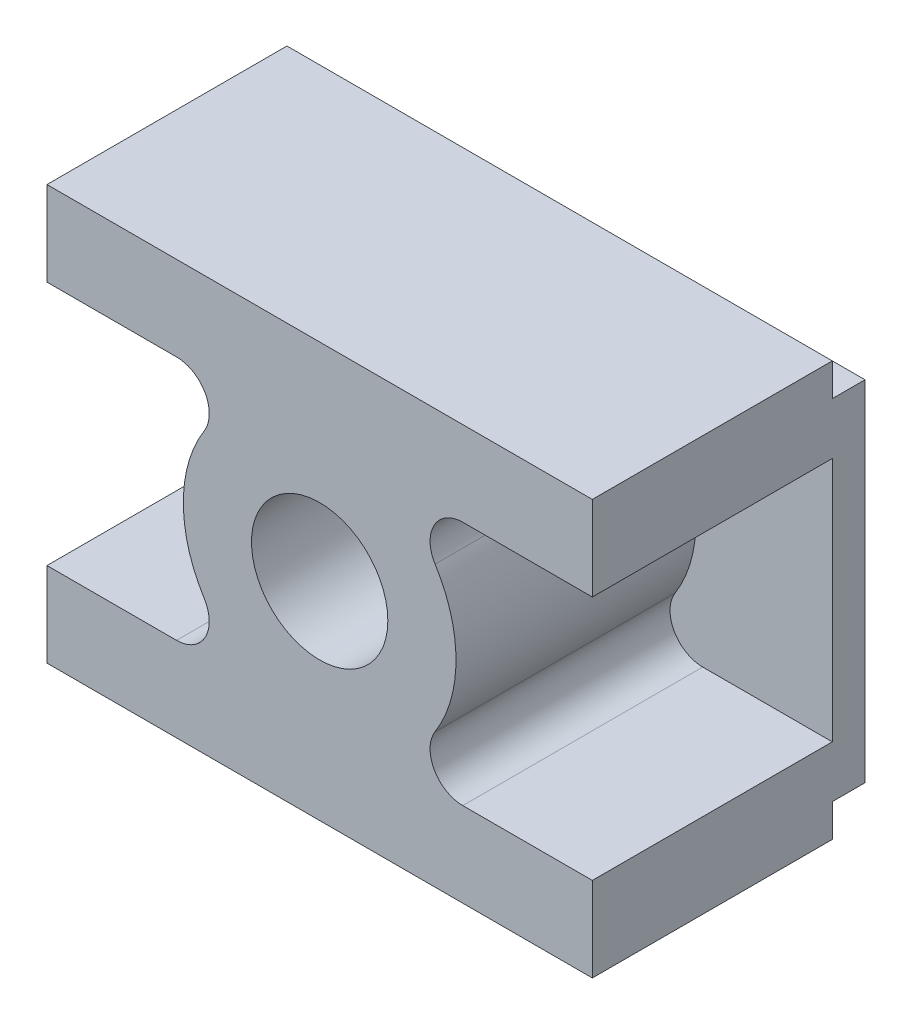
SolidWorks part; units mm, degrees
material "AISI 304"
ref_plane "Front Plane" through (0, 0, 0) normal (0, 0, 1) x (1, 0, 0)
ref_plane "Top Plane" through (0, 0, 0) normal (0, 1, 0) x (1, 0, 0)
ref_plane "Right Plane" through (0, 0, 0) normal (1, 0, 0) x (0, 0, -1)
sketch "Sketch1" plane through (0, 0, 0) normal (0, 0, 1) x (1, 0, 0)
  line L0 (26.244, 22.5) -> (50, 22.5)
  line L1 (-50, -38) -> (50, -38)
  line L2 (-50, -38) -> (-50, 38)
  line L3 (-50, 38) -> (50, 38)
  line L4 (50, -38) -> (50, 38)
  line L5 (-50, -38) -> (50, 38) construction
  line L6 (-50, 38) -> (50, -38) construction
  line L7 (-50, 22.5) -> (-26.244, 22.5)
  line L8 (-50, -22.5) -> (-26.244, -22.5)
  line L9 (26.244, -22.5) -> (50, -22.5)
  line L10 (-39.8812, 0) -> (43.0416, 0) construction
  arc A0 (-21.1646, 13.3065) -> (-21.1646, -13.3065) centre (0, 0) ccw
  circle A1 centre (0, 0) radius 12.5
  arc A2 (21.1646, -13.3065) -> (21.1646, 13.3065) centre (0, 0) ccw
  arc A3 (21.1646, -13.3065) -> (26.244, -22.5) centre (26.244, -16.5) ccw
  arc A4 (-21.1646, -13.3065) -> (-26.244, -22.5) centre (-26.244, -16.5) cw
  arc A5 (-21.1646, 13.3065) -> (-26.244, 22.5) centre (-26.244, 16.5) ccw
  arc A6 (26.244, 22.5) -> (21.1646, 13.3065) centre (26.244, 16.5) ccw
  point P0 (0, 0)
  point P15 (10.8972, -22.5)
  point P27 (10.8972, 22.5)
  dimension "D5" = 25
  dimension "D6" = 50
  dimension "D3" = 6
  dimension "D1" = 76
  dimension "D2" = 100
  dimension "D7" = 45
extrude "Boss-Extrude1" add sketch "Sketch1" along normal blind 50 contours A6 L0 L4 L3 L2 L7 A5 A0 A4 L8 L1 L9 A3 A2 A1
sketch "Sketch2" plane through (0, 0, 0) normal (0, 0, -1) x (-1, 0, 0)
  line L0 (50, -22.5) -> (26.244, -22.5) construction
  line L1 (50, 22.5) -> (26.244, 22.5) construction
  line L2 (-26.244, -22.5) -> (-50, -22.5) construction
  line L3 (-26.244, 22.5) -> (-50, 22.5) construction
  line L4 (50, -22.5) -> (26.244, -22.5)
  line L5 (50, 22.5) -> (26.244, 22.5)
  line L6 (-26.244, -22.5) -> (-50, -22.5)
  line L7 (-26.244, 22.5) -> (-50, 22.5)
  line L8 (-50, 22.5) -> (-50, -22.5)
  line L9 (50, 22.5) -> (50, -22.5)
  arc A0 (21.1646, -13.3065) -> (26.244, -22.5) centre (26.244, -16.5) ccw construction
  arc A1 (21.1646, -13.3065) -> (21.1646, 13.3065) centre (0, 0) ccw construction
  arc A2 (26.244, 22.5) -> (21.1646, 13.3065) centre (26.244, 16.5) ccw construction
  arc A3 (-26.244, -22.5) -> (-21.1646, -13.3065) centre (-26.244, -16.5) ccw construction
  arc A4 (-21.1646, 13.3065) -> (-21.1646, -13.3065) centre (0, 0) ccw construction
  arc A5 (-21.1646, 13.3065) -> (-26.244, 22.5) centre (-26.244, 16.5) ccw construction
  arc A6 (21.1646, -13.3065) -> (26.244, -22.5) centre (26.244, -16.5) ccw
  arc A7 (21.1646, -13.3065) -> (21.1646, 13.3065) centre (0, 0) ccw
  arc A8 (26.244, 22.5) -> (21.1646, 13.3065) centre (26.244, 16.5) ccw
  arc A9 (-26.244, -22.5) -> (-21.1646, -13.3065) centre (-26.244, -16.5) ccw
  arc A10 (-21.1646, 13.3065) -> (-21.1646, -13.3065) centre (0, 0) ccw
  arc A11 (-21.1646, 13.3065) -> (-26.244, 22.5) centre (-26.244, 16.5) ccw
extrude "Boss-Extrude2" add sketch "Sketch2" against normal blind 6
sketch "Sketch3" plane through (50, 0, 0) normal (1, 0, 0) x (0, 0, -1)
  line L1 (0, 38) -> (-6, 38)
  line L2 (0, 38) -> (0, 32)
  line L3 (0, 32) -> (-6, 32)
  line L4 (-6, 38) -> (-6, 32)
  line L5 (0, -38) -> (-6, -38)
  line L6 (0, -38) -> (0, -32)
  line L7 (0, -32) -> (-6, -32)
  line L8 (-6, -38) -> (-6, -32)
  dimension "D1" = 6
  dimension "D2" = 6
  dimension "D3" = 6
  dimension "D4" = 6
extrude "Cut-Extrude1" cut sketch "Sketch3" against normal through all
